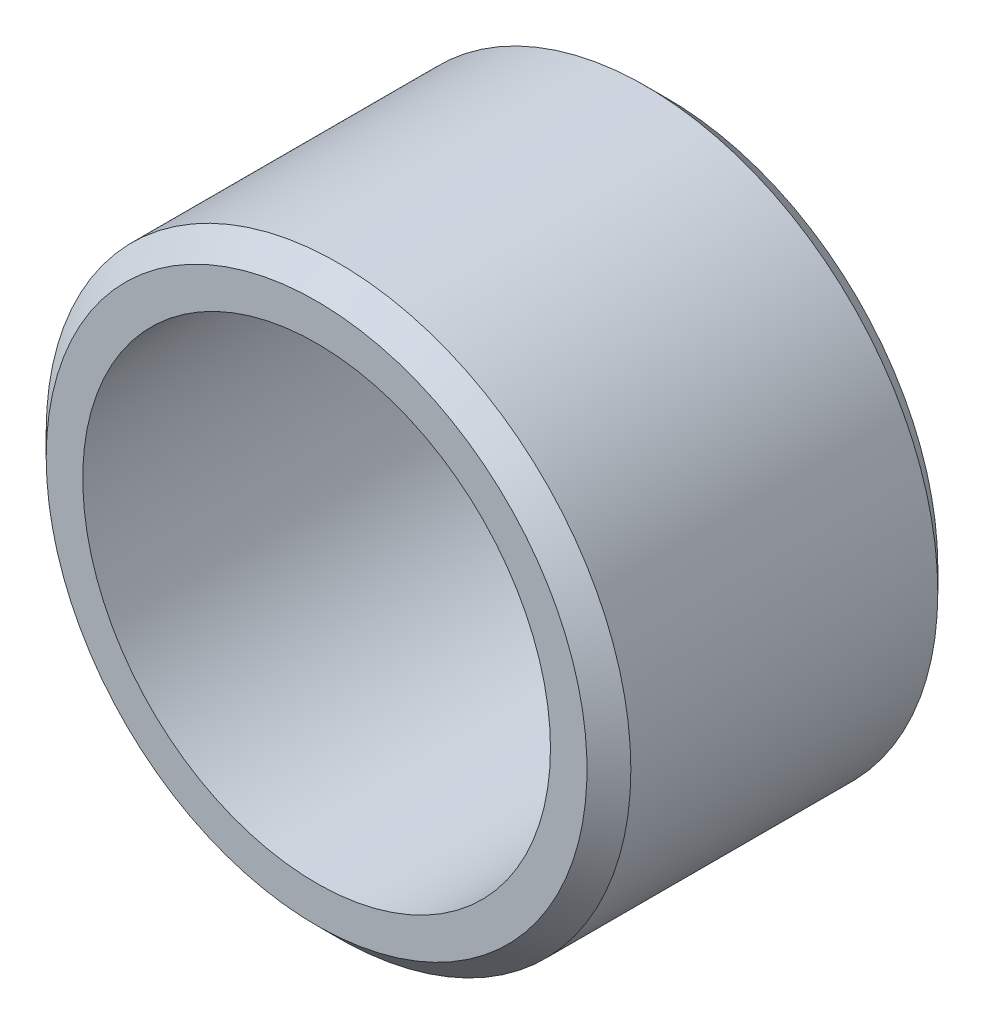
SolidWorks part; units mm, degrees
ref_plane "Front Plane" through (0, 0, 0) normal (0, 0, 1) x (1, 0, 0)
ref_plane "Top Plane" through (0, 0, 0) normal (0, 1, 0) x (1, 0, 0)
ref_plane "Right Plane" through (0, 0, 0) normal (1, 0, 0) x (0, 0, -1)
sketch "Sketch1" plane through (0, 0, 0) normal (1, 0, 0) x (0, 0, -1)
  line L0 (-4.7625, 0) -> (4.7625, 0) construction
  line L1 (4.7625, 7.9375) -> (4.7625, -7.9375) construction
  line L2 (-4.7625, 7.9375) -> (-4.7625, -7.9375) construction
  line L3 (4.7625, 7.9375) -> (-4.7625, 7.9375) construction
  line L4 (4.7625, -7.9375) -> (-4.7625, -7.9375) construction
  line L5 (-4.7625, 6.35) -> (4.7625, 6.35) construction
  line L6 (-4.7625, -6.35) -> (4.7625, -6.35) construction
  point P2 (0, 0)
  point P7 (-4.7625, 0)
  point P8 (-4.7625, -6.35)
  point P9 (4.7625, 0)
  point P11 (-4.7625, 6.35)
  dimension "OD" = 15.875
  dimension "ID" = 12.7
  dimension "Length" = 9.525
sketch "Sketch2" plane through (0, 0, 0) normal (0, 0, 1) x (1, 0, 0)
  line L0 (-7.9375, 0) -> (7.9375, 0) construction
  line L1 (0, -7.9375) -> (0, 7.9375) construction
  circle A0 centre (0, 0) radius 6.35 construction
  circle A1 centre (0, 0) radius 7.9375 construction
  point P16 (0, 0)
  dimension "ID" = 12.7
  dimension "OD" = 15.875
sketch "Sketch3" plane through (0, 0, 0) normal (1, 0, 0) x (0, 0, -1)
  line L0 (-4.7625, 6.35) -> (4.7625, 6.35)
  line L1 (4.7625, 7.9375) -> (4.7625, -7.9375) construction
  line L2 (4.7625, 6.35) -> (4.7625, 7.9375)
  line L5 (4.7625, 7.9375) -> (-4.7625, 7.9375)
  line L6 (-4.7625, 7.9375) -> (-4.7625, 6.35)
  line L7 (-4.7625, 0) -> (4.7625, 0) construction
revolve "Revolve1" add sketch "Sketch3" angle 360 about L7
chamfer "Chamfer1" distance 0.5953 angle 45 2 edges at (7.9375, 0, 4.7625) (7.9375, 0, -4.7625)
equation "\"D1@Chamfer1\"=((\"OD@Sketch1\"-\"ID@Sketch1\")/2)*.375"
